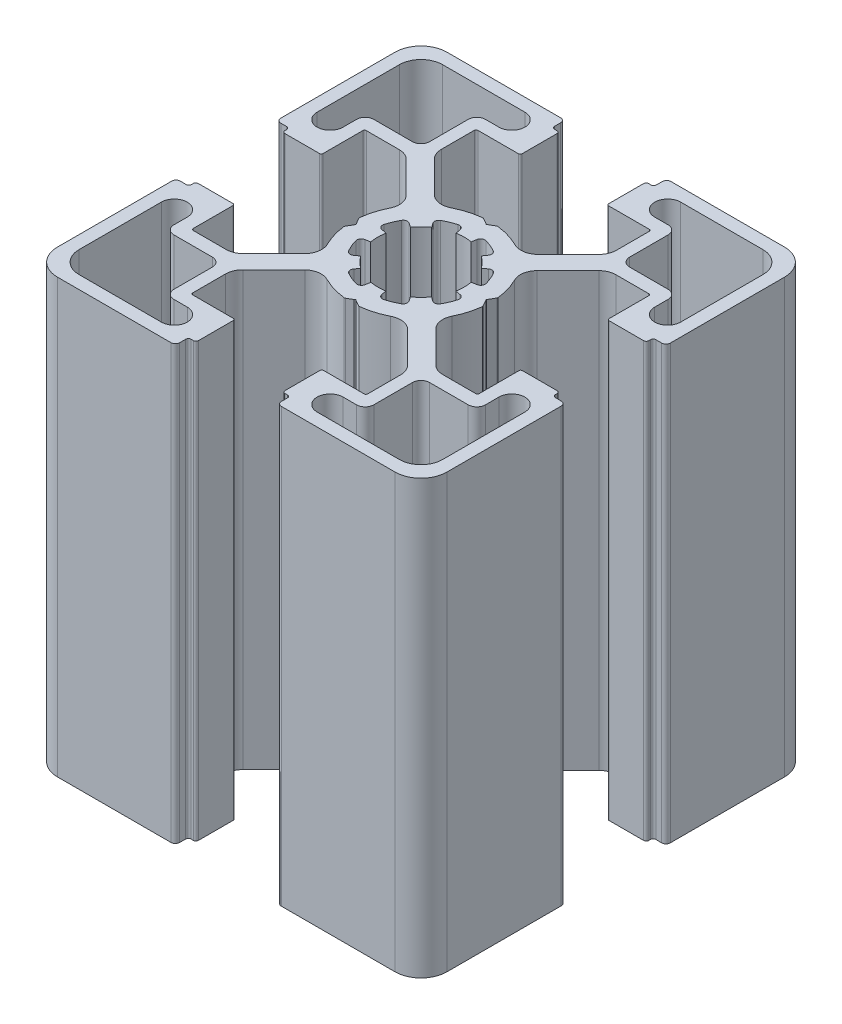
SolidWorks part; units mm, degrees
ref_plane "Front Plane" through (0, 0, 0) normal (0, 0, 1) x (1, 0, 0)
ref_plane "Top Plane" through (0, 0, 0) normal (0, 1, 0) x (1, 0, 0)
ref_plane "Right Plane" through (0, 0, 0) normal (1, 0, 0) x (0, 0, -1)
sketch "Sketch1" plane through (0, 0, 0) normal (0, 1, 0) x (1, 0, 0)
  line L106 (-18, 9.0002) -> (-18, 10.55)
  line L107 (-21, 18.5) -> (-21, 9.0002)
  line L108 (-9, 21) -> (-18.5, 21)
  line L109 (-10.55, 18) -> (-9, 18)
  line L110 (0.9675, 5.4811) -> (0.8674, 4.9242)
  line L111 (2.864, 4.0985) -> (3.1913, 4.5626)
  line L112 (4.5668, 3.2081) -> (4.0897, 2.8765)
  line L113 (4.9205, 0.8878) -> (5.4897, 0.9862)
  line L114 (5.4898, -0.9862) -> (4.9205, -0.8878)
  line L115 (4.0897, -2.8765) -> (4.5668, -3.2082)
  line L116 (3.1914, -4.5627) -> (2.864, -4.0985)
  line L117 (0.8674, -4.9242) -> (0.9675, -5.4811)
  line L118 (-0.9675, -5.4811) -> (-0.8674, -4.9242)
  line L119 (-2.864, -4.0985) -> (-3.1913, -4.5626)
  line L120 (-4.5668, -3.2082) -> (-4.0897, -2.8765)
  line L121 (-4.9205, -0.8878) -> (-5.4897, -0.9862)
  line L122 (-5.4899, 0.9862) -> (-4.9205, 0.8878)
  line L123 (-4.0897, 2.8765) -> (-4.5668, 3.2081)
  line L124 (-3.1914, 4.5627) -> (-2.864, 4.0985)
  line L125 (-0.8674, 4.9242) -> (-0.9675, 5.4811)
  line L126 (-11.55, 12.55) -> (-11.55, 17)
  line L127 (-17, 11.55) -> (-12.55, 11.55)
  line L128 (-21, -9.0002) -> (-21, -18.5)
  line L129 (-18, -10.55) -> (-18, -9.0002)
  line L130 (-12.55, -11.55) -> (-17, -11.55)
  line L131 (-11.55, -17) -> (-11.55, -12.55)
  line L132 (-9, -18) -> (-10.55, -18)
  line L133 (-18.5, -21) -> (-9, -21)
  line L134 (21, 9.0002) -> (21, 18.5)
  line L135 (18, 10.55) -> (18, 9.0002)
  line L136 (12.55, 11.55) -> (17, 11.55)
  line L137 (11.55, 17) -> (11.55, 12.55)
  line L138 (9, 18) -> (10.55, 18)
  line L139 (18.5, 21) -> (9, 21)
  line L140 (17, -11.55) -> (12.55, -11.55)
  line L141 (18, -9.0002) -> (18, -10.55)
  line L142 (21, -18.5) -> (21, -9.0002)
  line L143 (9, -21) -> (18.5, -21)
  line L144 (10.55, -18) -> (9, -18)
  line L145 (11.55, -12.55) -> (11.55, -17)
  line L146 (7.5635, 5.8587) -> (11.1298, 9.425)
  line L147 (12.5048, 9.9945) -> (16.3169, 9.9945)
  line L148 (16.5169, 9.7945) -> (16.5169, 5.2)
  line L149 (16.7169, 5) -> (20.7196, 5)
  line L150 (21.0196, 5.3) -> (21.0196, 5.5)
  line L151 (21.3196, 5.8) -> (22, 5.8)
  line L152 (22.5, 6.3) -> (22.5, 19.5)
  line L153 (19.5, 22.5) -> (6.3757, 22.5)
  line L154 (5.8757, 22) -> (5.8757, 21.3)
  line L155 (5.5757, 21) -> (5.3, 21)
  line L156 (5, 20.7) -> (5, 16.6668)
  line L157 (5.2, 16.4668) -> (9.9054, 16.4668)
  line L158 (10.1054, 16.2668) -> (10.1054, 12.4716)
  line L159 (9.5196, 11.0574) -> (5.9449, 7.4827)
  line L160 (0.7548, 7.9748) -> (0.1126, 7.6069)
  line L161 (-0.1126, 7.6069) -> (-0.7547, 7.9748)
  line L162 (-5.9449, 7.4827) -> (-9.5196, 11.0574)
  line L163 (-10.1054, 12.4716) -> (-10.1054, 16.2668)
  line L164 (-9.9054, 16.4668) -> (-5.2, 16.4668)
  line L165 (-5, 16.6668) -> (-5, 20.7)
  line L166 (-5.3, 21) -> (-5.5757, 21)
  line L167 (-5.8757, 21.3) -> (-5.8757, 22)
  line L168 (-6.3757, 22.5) -> (-19.5, 22.5)
  line L169 (-22.5, 19.5) -> (-22.5, 6.3)
  line L170 (-22, 5.8) -> (-21.3196, 5.8)
  line L171 (-21.0196, 5.5) -> (-21.0196, 5.3)
  line L172 (-20.7196, 5) -> (-16.7169, 5)
  line L173 (-16.5169, 5.2) -> (-16.5169, 9.7945)
  line L174 (-16.3169, 9.9945) -> (-12.5048, 9.9945)
  line L175 (-11.1298, 9.425) -> (-7.5635, 5.8587)
  line L176 (-7.974, 0.7926) -> (-7.5401, 0.0468)
  line L177 (-7.5401, -0.0468) -> (-7.974, -0.7926)
  line L178 (-7.5635, -5.8587) -> (-11.1298, -9.425)
  line L179 (-12.5048, -9.9945) -> (-16.3169, -9.9945)
  line L180 (-16.5169, -9.7945) -> (-16.5169, -5.2)
  line L181 (-16.7169, -5) -> (-20.7196, -5)
  line L182 (-21.0196, -5.3) -> (-21.0196, -5.5)
  line L183 (-21.3196, -5.8) -> (-22, -5.8)
  line L184 (-22.5, -6.3) -> (-22.5, -19.5)
  line L185 (-19.5, -22.5) -> (-6.3757, -22.5)
  line L186 (-5.8757, -22) -> (-5.8757, -21.3)
  line L187 (-5.5757, -21) -> (-5.3, -21)
  line L188 (-5, -20.7) -> (-5, -16.6668)
  line L189 (-5.2, -16.4668) -> (-9.9054, -16.4668)
  line L190 (-10.1054, -16.2668) -> (-10.1054, -12.4716)
  line L191 (-9.5196, -11.0574) -> (-5.9449, -7.4827)
  line L192 (-0.7547, -7.9748) -> (-0.1126, -7.6069)
  line L193 (0.1126, -7.6069) -> (0.7548, -7.9748)
  line L194 (5.9449, -7.4827) -> (9.5196, -11.0574)
  line L195 (10.1054, -12.4716) -> (10.1054, -16.2668)
  line L196 (9.9054, -16.4668) -> (5.2, -16.4668)
  line L197 (5, -16.6668) -> (5, -20.7)
  line L198 (5.3, -21) -> (5.5757, -21)
  line L199 (5.8757, -21.3) -> (5.8757, -22)
  line L200 (6.3757, -22.5) -> (19.5, -22.5)
  line L201 (22.5, -19.5) -> (22.5, -6.3)
  line L202 (22, -5.8) -> (21.3196, -5.8)
  line L203 (21.0196, -5.5) -> (21.0196, -5.3)
  line L204 (20.7196, -5) -> (16.7169, -5)
  line L205 (16.5169, -5.2) -> (16.5169, -9.7945)
  line L206 (16.3169, -9.9945) -> (12.5048, -9.9945)
  line L207 (11.1298, -9.425) -> (7.5635, -5.8587)
  line L208 (7.974, -0.7926) -> (7.5401, -0.0468)
  line L209 (7.5401, 0.0468) -> (7.974, 0.7926)
  arc A140 (-17, 11.55) -> (-18, 10.55) centre (-17, 10.55) ccw
  arc A141 (-21, 9.0002) -> (-18, 9.0002) centre (-19.5, 9.0002) ccw
  arc A142 (-18.5, 21) -> (-21, 18.5) centre (-18.5, 18.5) ccw
  arc A143 (-9, 18) -> (-9, 21) centre (-9, 19.5) ccw
  arc A144 (-10.55, 18) -> (-11.55, 17) centre (-10.55, 17) ccw
  arc A145 (-12.55, 11.55) -> (-11.55, 12.55) centre (-12.55, 12.55) ccw
  arc A146 (-21, -18.5) -> (-18.5, -21) centre (-18.5, -18.5) ccw
  arc A147 (-18, -9.0002) -> (-21, -9.0002) centre (-19.5, -9.0002) ccw
  arc A148 (-18, -10.55) -> (-17, -11.55) centre (-17, -10.55) ccw
  arc A149 (-11.55, -12.55) -> (-12.55, -11.55) centre (-12.55, -12.55) ccw
  arc A150 (-11.55, -17) -> (-10.55, -18) centre (-10.55, -17) ccw
  arc A151 (-9, -21) -> (-9, -18) centre (-9, -19.5) ccw
  arc A152 (0.8674, 4.9242) -> (-0.8674, 4.9242) centre (0, 0) ccw
  arc A153 (1.5951, 5.8941) -> (0.9675, 5.4811) centre (1.4627, 5.4119) ccw
  arc A154 (3.0417, 5.301) -> (1.5951, 5.8941) centre (0.0235, 0) ccw
  arc A155 (3.1913, 4.5626) -> (3.0417, 5.301) centre (2.7943, 4.8665) ccw
  arc A156 (4.0897, 2.8765) -> (2.864, 4.0985) centre (0, 0) ccw
  arc A157 (5.3025, 3.0565) -> (4.5668, 3.2081) centre (4.868, 2.8091) ccw
  arc A158 (5.906, 1.6142) -> (5.3025, 3.0565) centre (0.0235, 0) ccw
  arc A159 (5.4897, 0.9862) -> (5.906, 1.6142) centre (5.4239, 1.4819) ccw
  arc A160 (4.9205, -0.8878) -> (4.9205, 0.8878) centre (0, 0) ccw
  arc A161 (5.906, -1.6142) -> (5.4898, -0.9862) centre (5.4239, -1.4819) ccw
  arc A162 (5.3025, -3.0564) -> (5.906, -1.6142) centre (0.0235, 0) ccw
  arc A163 (4.5668, -3.2082) -> (5.3025, -3.0564) centre (4.868, -2.8091) ccw
  arc A164 (2.864, -4.0985) -> (4.0897, -2.8765) centre (0, 0) ccw
  arc A165 (3.0416, -5.301) -> (3.1914, -4.5627) centre (2.7943, -4.8665) ccw
  arc A166 (1.5951, -5.8941) -> (3.0416, -5.301) centre (0.0235, 0) ccw
  arc A167 (0.9675, -5.4811) -> (1.5951, -5.8941) centre (1.4627, -5.4119) ccw
  arc A168 (-0.8674, -4.9242) -> (0.8674, -4.9242) centre (0, 0) ccw
  arc A169 (-1.5951, -5.8941) -> (-0.9675, -5.4811) centre (-1.4627, -5.4119) ccw
  arc A170 (-3.0416, -5.301) -> (-1.5951, -5.8941) centre (-0.0235, 0) ccw
  arc A171 (-3.1913, -4.5626) -> (-3.0416, -5.301) centre (-2.7943, -4.8665) ccw
  arc A172 (-4.0897, -2.8765) -> (-2.864, -4.0985) centre (0, 0) ccw
  arc A173 (-5.3025, -3.0565) -> (-4.5668, -3.2082) centre (-4.868, -2.8091) ccw
  arc A174 (-5.906, -1.6142) -> (-5.3025, -3.0565) centre (-0.0235, 0) ccw
  arc A175 (-5.4897, -0.9862) -> (-5.906, -1.6142) centre (-5.4239, -1.4819) ccw
  arc A176 (-4.9205, 0.8878) -> (-4.9205, -0.8878) centre (0, 0) ccw
  arc A177 (-5.906, 1.6141) -> (-5.4899, 0.9862) centre (-5.4239, 1.4818) ccw
  arc A178 (-5.3025, 3.0564) -> (-5.906, 1.6141) centre (-0.0235, 0) ccw
  arc A179 (-4.5668, 3.2081) -> (-5.3025, 3.0564) centre (-4.868, 2.8091) ccw
  arc A180 (-2.864, 4.0985) -> (-4.0897, 2.8765) centre (0, 0) ccw
  arc A181 (-3.0417, 5.301) -> (-3.1914, 4.5627) centre (-2.7943, 4.8665) ccw
  arc A182 (-1.5951, 5.8941) -> (-3.0417, 5.301) centre (-0.0235, 0) ccw
  arc A183 (-0.9675, 5.4811) -> (-1.5951, 5.8941) centre (-1.4627, 5.4119) ccw
  arc A184 (21, 18.5) -> (18.5, 21) centre (18.5, 18.5) ccw
  arc A185 (18, 9.0002) -> (21, 9.0002) centre (19.5, 9.0002) ccw
  arc A186 (18, 10.55) -> (17, 11.55) centre (17, 10.55) ccw
  arc A187 (11.55, 12.55) -> (12.55, 11.55) centre (12.55, 12.55) ccw
  arc A188 (11.55, 17) -> (10.55, 18) centre (10.55, 17) ccw
  arc A189 (9, 21) -> (9, 18) centre (9, 19.5) ccw
  arc A190 (12.55, -11.55) -> (11.55, -12.55) centre (12.55, -12.55) ccw
  arc A191 (17, -11.55) -> (18, -10.55) centre (17, -10.55) ccw
  arc A192 (21, -9.0002) -> (18, -9.0002) centre (19.5, -9.0002) ccw
  arc A193 (18.5, -21) -> (21, -18.5) centre (18.5, -18.5) ccw
  arc A194 (9, -18) -> (9, -21) centre (9, -19.5) ccw
  arc A195 (10.55, -18) -> (11.55, -17) centre (10.55, -17) ccw
  arc A196 (7.9999, 0.9154) -> (7.2004, 3.6119) centre (0.0496, 0.0249) ccw
  arc A197 (7.5635, 5.8587) -> (7.2004, 3.6119) centre (8.9385, 4.4837) ccw
  arc A198 (12.5048, 9.9945) -> (11.1298, 9.425) centre (12.5048, 8.05) ccw
  arc A199 (16.5169, 9.7945) -> (16.3169, 9.9945) centre (16.3169, 9.7945) ccw
  arc A200 (16.5169, 5.2) -> (16.7169, 5) centre (16.7169, 5.2) ccw
  arc A201 (20.7196, 5) -> (21.0196, 5.3) centre (20.7196, 5.3) ccw
  arc A202 (21.3196, 5.8) -> (21.0196, 5.5) centre (21.3196, 5.5) ccw
  arc A203 (22, 5.8) -> (22.5, 6.3) centre (22, 6.3) ccw
  arc A204 (22.5, 19.5) -> (19.5, 22.5) centre (19.5, 19.5) ccw
  arc A205 (6.3757, 22.5) -> (5.8757, 22) centre (6.3757, 22) ccw
  arc A206 (5.5757, 21) -> (5.8757, 21.3) centre (5.5757, 21.3) ccw
  arc A207 (5.3, 21) -> (5, 20.7) centre (5.3, 20.7) ccw
  arc A208 (5, 16.6668) -> (5.2, 16.4668) centre (5.2, 16.6668) ccw
  arc A209 (10.1054, 16.2668) -> (9.9054, 16.4668) centre (9.9054, 16.2668) ccw
  arc A210 (9.5196, 11.0574) -> (10.1054, 12.4716) centre (8.1054, 12.4716) ccw
  arc A211 (3.6665, 7.1733) -> (5.9449, 7.4827) centre (4.5855, 8.9496) ccw
  arc A212 (3.6665, 7.1733) -> (0.8753, 8.0001) centre (0.0235, 0) ccw
  arc A213 (0.8753, 8.0001) -> (0.7548, 7.9748) centre (0.8542, 7.8013) ccw
  arc A214 (0, 7.531) -> (0.1126, 7.6069) centre (-0.0489, 7.7249) ccw
  arc A215 (-0.1126, 7.6069) -> (0, 7.531) centre (0.0489, 7.7249) ccw
  arc A216 (-0.7547, 7.9748) -> (-0.8753, 8.0001) centre (-0.8542, 7.8013) ccw
  arc A217 (-0.8753, 8.0001) -> (-3.6665, 7.1733) centre (-0.0235, 0) ccw
  arc A218 (-5.9449, 7.4827) -> (-3.6665, 7.1733) centre (-4.5855, 8.9496) ccw
  arc A219 (-10.1054, 12.4716) -> (-9.5196, 11.0574) centre (-8.1054, 12.4716) ccw
  arc A220 (-9.9054, 16.4668) -> (-10.1054, 16.2668) centre (-9.9054, 16.2668) ccw
  arc A221 (-5.2, 16.4668) -> (-5, 16.6668) centre (-5.2, 16.6668) ccw
  arc A222 (-5, 20.7) -> (-5.3, 21) centre (-5.3, 20.7) ccw
  arc A223 (-5.8757, 21.3) -> (-5.5757, 21) centre (-5.5757, 21.3) ccw
  arc A224 (-5.8757, 22) -> (-6.3757, 22.5) centre (-6.3757, 22) ccw
  arc A225 (-19.5, 22.5) -> (-22.5, 19.5) centre (-19.5, 19.5) ccw
  arc A226 (-22.5, 6.3) -> (-22, 5.8) centre (-22, 6.3) ccw
  arc A227 (-21.0196, 5.5) -> (-21.3196, 5.8) centre (-21.3196, 5.5) ccw
  arc A228 (-21.0196, 5.3) -> (-20.7196, 5) centre (-20.7196, 5.3) ccw
  arc A229 (-16.7169, 5) -> (-16.5169, 5.2) centre (-16.7169, 5.2) ccw
  arc A230 (-16.3169, 9.9945) -> (-16.5169, 9.7945) centre (-16.3169, 9.7945) ccw
  arc A231 (-11.1298, 9.425) -> (-12.5048, 9.9945) centre (-12.5048, 8.05) ccw
  arc A232 (-7.2004, 3.6119) -> (-7.5635, 5.8587) centre (-8.9385, 4.4837) ccw
  arc A233 (-7.2004, 3.6119) -> (-7.9999, 0.9154) centre (-0.0496, 0.0249) ccw
  arc A234 (-7.9999, 0.9154) -> (-7.974, 0.7926) centre (-7.8011, 0.8932) ccw
  arc A235 (-7.5313, 0) -> (-7.5401, 0.0468) centre (-7.7309, -0.013) ccw
  arc A236 (-7.5401, -0.0468) -> (-7.5313, 0) centre (-7.7309, 0.013) ccw
  arc A237 (-7.974, -0.7926) -> (-7.9999, -0.9154) centre (-7.8011, -0.8932) ccw
  arc A238 (-7.9999, -0.9154) -> (-7.2004, -3.6119) centre (-0.0496, -0.0249) ccw
  arc A239 (-7.5635, -5.8587) -> (-7.2004, -3.6119) centre (-8.9385, -4.4837) ccw
  arc A240 (-12.5048, -9.9945) -> (-11.1298, -9.425) centre (-12.5048, -8.05) ccw
  arc A241 (-16.5169, -9.7945) -> (-16.3169, -9.9945) centre (-16.3169, -9.7945) ccw
  arc A242 (-16.5169, -5.2) -> (-16.7169, -5) centre (-16.7169, -5.2) ccw
  arc A243 (-20.7196, -5) -> (-21.0196, -5.3) centre (-20.7196, -5.3) ccw
  arc A244 (-21.3196, -5.8) -> (-21.0196, -5.5) centre (-21.3196, -5.5) ccw
  arc A245 (-22, -5.8) -> (-22.5, -6.3) centre (-22, -6.3) ccw
  arc A246 (-22.5, -19.5) -> (-19.5, -22.5) centre (-19.5, -19.5) ccw
  arc A247 (-6.3757, -22.5) -> (-5.8757, -22) centre (-6.3757, -22) ccw
  arc A248 (-5.5757, -21) -> (-5.8757, -21.3) centre (-5.5757, -21.3) ccw
  arc A249 (-5.3, -21) -> (-5, -20.7) centre (-5.3, -20.7) ccw
  arc A250 (-5, -16.6668) -> (-5.2, -16.4668) centre (-5.2, -16.6668) ccw
  arc A251 (-10.1054, -16.2668) -> (-9.9054, -16.4668) centre (-9.9054, -16.2668) ccw
  arc A252 (-9.5196, -11.0574) -> (-10.1054, -12.4716) centre (-8.1054, -12.4716) ccw
  arc A253 (-3.6665, -7.1733) -> (-5.9449, -7.4827) centre (-4.5855, -8.9496) ccw
  arc A254 (-3.6665, -7.1733) -> (-0.8753, -8.0001) centre (-0.0235, 0) ccw
  arc A255 (-0.8753, -8.0001) -> (-0.7547, -7.9748) centre (-0.8542, -7.8013) ccw
  arc A256 (0, -7.531) -> (-0.1126, -7.6069) centre (0.0489, -7.7249) ccw
  arc A257 (0.1126, -7.6069) -> (0, -7.531) centre (-0.0489, -7.7249) ccw
  arc A258 (0.7548, -7.9748) -> (0.8753, -8.0001) centre (0.8542, -7.8012) ccw
  arc A259 (0.8753, -8.0001) -> (3.6665, -7.1733) centre (0.0235, 0) ccw
  arc A260 (5.9449, -7.4827) -> (3.6665, -7.1733) centre (4.5855, -8.9496) ccw
  arc A261 (10.1054, -12.4716) -> (9.5196, -11.0574) centre (8.1054, -12.4716) ccw
  arc A262 (9.9054, -16.4668) -> (10.1054, -16.2668) centre (9.9054, -16.2668) ccw
  arc A263 (5.2, -16.4668) -> (5, -16.6668) centre (5.2, -16.6668) ccw
  arc A264 (5, -20.7) -> (5.3, -21) centre (5.3, -20.7) ccw
  arc A265 (5.8757, -21.3) -> (5.5757, -21) centre (5.5757, -21.3) ccw
  arc A266 (5.8757, -22) -> (6.3757, -22.5) centre (6.3757, -22) ccw
  arc A267 (19.5, -22.5) -> (22.5, -19.5) centre (19.5, -19.5) ccw
  arc A268 (22.5, -6.3) -> (22, -5.8) centre (22, -6.3) ccw
  arc A269 (21.0196, -5.5) -> (21.3196, -5.8) centre (21.3196, -5.5) ccw
  arc A270 (21.0196, -5.3) -> (20.7196, -5) centre (20.7196, -5.3) ccw
  arc A271 (16.7169, -5) -> (16.5169, -5.2) centre (16.7169, -5.2) ccw
  arc A272 (16.3169, -9.9945) -> (16.5169, -9.7945) centre (16.3169, -9.7945) ccw
  arc A273 (11.1298, -9.425) -> (12.5048, -9.9945) centre (12.5048, -8.05) ccw
  arc A274 (7.2004, -3.6119) -> (7.5635, -5.8587) centre (8.9385, -4.4837) ccw
  arc A275 (7.2004, -3.6119) -> (7.9999, -0.9154) centre (0.0496, -0.0249) ccw
  arc A276 (7.9999, -0.9154) -> (7.974, -0.7926) centre (7.8011, -0.8932) ccw
  arc A277 (7.5313, 0) -> (7.5401, -0.0468) centre (7.7309, 0.013) ccw
  arc A278 (7.5401, 0.0468) -> (7.5313, 0) centre (7.7309, -0.013) ccw
  arc A279 (7.974, 0.7926) -> (7.9999, 0.9154) centre (7.8011, 0.8932) ccw
  point P384 (19.5, -19.5)
extrude "Boss-Extrude1" add sketch "Sketch1" along normal blind 50
